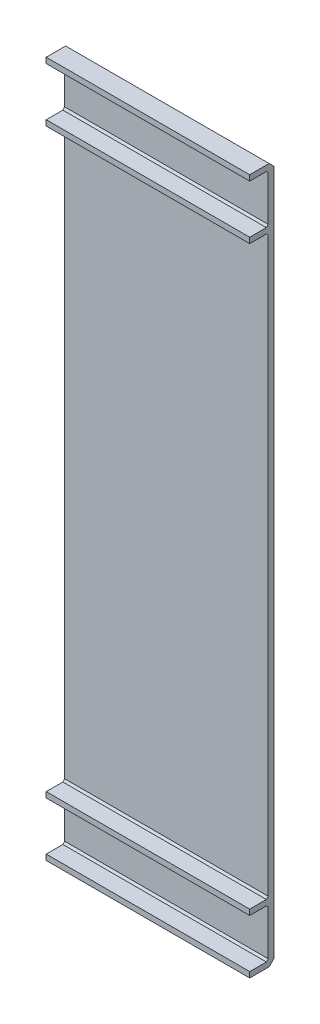
SolidWorks part; units mm, degrees
ref_plane "Alzado" through (0, 0, 0) normal (1, 0, 0) x (0, 1, 0)
ref_plane "Planta" through (0, 0, 0) normal (0, 0, 1) x (0, 1, 0)
ref_plane "Vista lateral" through (0, 0, 0) normal (0, 1, 0) x (-1, 0, 0)
sketch "Croquis1" plane through (0, 0, 0) normal (0, 0, 1) x (0, 1, 0)
  line L1 (-75.2, 22) -> (75.2, 22)
  line L2 (-75.2, 22) -> (-75.2, -22)
  line L3 (-75.2, -22) -> (75.2, -22)
  line L4 (75.2, 22) -> (75.2, -22)
  line L5 (-75.2, 22) -> (75.2, -22) construction
  line L6 (-75.2, -22) -> (75.2, 22) construction
  point P0 (0, 0)
  dimension "D1" = 44
  dimension "D2" = 150.4
extrude "Saliente-Extruir1" add sketch "Croquis1" along normal blind 1.2
sketch "Croquis2" plane through (0, 0, 1.2) normal (0, 0, 1) x (1, 0, 0)
  line L0 (22, -75.2) -> (22, 75.2) construction
  line L1 (-22, 75.2) -> (22, 75.2)
  line L2 (-22, 75.2) -> (-22, 74)
  line L3 (-22, 74) -> (22, 74)
  line L4 (22, 75.2) -> (22, 74)
  line L5 (-22, 75.2) -> (-22, -75.2) construction
  line L6 (-22, -75.2) -> (22, -75.2)
  line L7 (-22, -75.2) -> (-22, -74)
  line L8 (-22, -74) -> (22, -74)
  line L9 (22, -75.2) -> (22, -74)
  line L10 (-22, -62.3) -> (22, -62.3)
  line L11 (-22, -62.3) -> (-22, -63.5)
  line L12 (-22, -63.5) -> (22, -63.5)
  line L13 (22, -62.3) -> (22, -63.5)
  line L15 (-22, 63.5) -> (22, 63.5)
  line L16 (-22, 63.5) -> (-22, 62.3)
  line L17 (-22, 62.3) -> (22, 62.3)
  line L18 (22, 63.5) -> (22, 62.3)
  dimension "D1" = 1.2
  dimension "D2" = 10.5
  dimension "D3" = 10.5
  dimension "D4" = 1.2
extrude "Saliente-Extruir2" add sketch "Croquis2" along normal blind 4
chamfer "Chaflán1" distance 0.4 angle 45 6 edges at (0, 74, 1.2) (0, 62.3, 1.2) (0, 63.5, 1.2) (0, -62.3, 1.2) (0, -74, 1.2) (0, -63.5, 1.2)
chamfer "Chaflán2" distance 1 angle 45 2 edges at (0, 75.2, 0) (0, -75.2, 0)
